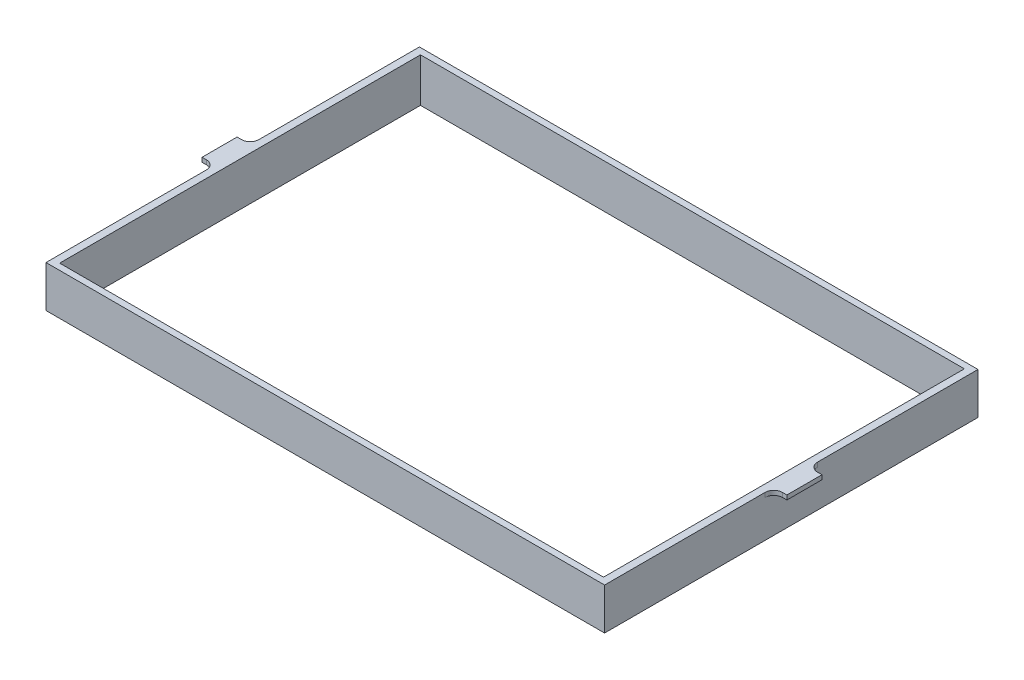
SolidWorks part; units mm, degrees
ref_plane "Front Plane" through (0, 0, 0) normal (0, 0, 1) x (1, 0, 0)
ref_plane "Top Plane" through (0, 0, 0) normal (0, 1, 0) x (1, 0, 0)
ref_plane "Right Plane" through (0, 0, 0) normal (1, 0, 0) x (0, 0, -1)
sketch "Sketch1" plane through (0, 0, 0) normal (0, 1, 0) x (1, 0, 0)
  line L0 (63.88, 42.735) -> (-63.88, 42.735)
  line L1 (63.88, 42.735) -> (63.88, -42.735)
  line L2 (63.88, -42.735) -> (-63.88, -42.735)
  line L3 (-63.88, 42.735) -> (-63.88, -42.735)
  line L4 (63.88, 42.735) -> (-63.88, -42.735) construction
  line L5 (63.88, -42.735) -> (-63.88, 42.735) construction
  point P0 (0, 0)
  dimension "D1" = 127.76
  dimension "D2" = 85.47
sketch "Sketch2" plane through (0, 0, 0) normal (0, 1, 0) x (1, 0, 0)
  line L0 (63.88, 42.735) -> (63.88, -42.735) construction
  line L1 (63.88, -42.735) -> (-63.88, -42.735) construction
  line L2 (-63.88, 42.735) -> (-63.88, -42.735) construction
  line L3 (63.88, 42.735) -> (-63.88, 42.735) construction
  line L4 (63.88, 42.735) -> (63.88, -42.735) construction
  line L5 (63.88, -42.735) -> (-63.88, -42.735) construction
  line L6 (-63.88, 42.735) -> (-63.88, -42.735) construction
  line L7 (63.88, 42.735) -> (-63.88, 42.735) construction
  line L8 (63.78, 42.635) -> (-63.78, 42.635)
  line L9 (-63.78, 42.635) -> (-63.78, -42.635)
  line L10 (63.78, -42.635) -> (-63.78, -42.635)
  line L11 (63.78, 42.635) -> (63.78, -42.635)
  line L12 (63.88, -42.735) -> (-63.88, 42.735) construction
  line L13 (62.1, -41.2) -> (-62.1, -41.2)
  line L14 (62.1, -41.2) -> (62.1, 41.2)
  line L15 (62.1, 41.2) -> (-62.1, 41.2)
  line L16 (-62.1, -41.2) -> (-62.1, 41.2)
  line L17 (62.1, -41.2) -> (-62.1, 41.2) construction
  line L18 (62.1, 41.2) -> (-62.1, -41.2) construction
  point P8 (0, 0)
  dimension "D2" = 82.4
  dimension "D3" = 124.2
  dimension "D1" = 0.1
extrude "Boss-Extrude1" add sketch "Sketch2" along normal blind 10 contours L11 L8 L9 L10 L13 L16 L15 L14
sketch "Sketch3" plane through (-63.78, 0, 0) normal (-1, 0, 0) x (0, 0, 1)
  line L0 (-42.635, 10) -> (42.635, 10) construction
  line L1 (4, 10) -> (-4, 10)
  line L2 (4, 10) -> (4, 9)
  line L3 (4, 9) -> (-4, 9)
  line L4 (-4, 10) -> (-4, 9)
  line L5 (4, 10) -> (-4, 9) construction
  line L6 (4, 9) -> (-4, 10) construction
  line L7 (-42.735, 0) -> (42.735, 0) construction
  point P0 (0, 9.5)
  dimension "D1" = 9
  dimension "D2" = 8
extrude "Boss-Extrude2" add sketch "Sketch3" along normal blind 3
chamfer "Chamfer1" distance 0.5 angle 45 4 edges at (0, 0, 42.635) (63.78, 0, 0) (0, 0, -42.635) (-63.78, 0, 0)
mirror "Mirror1" about plane through (0, 0, 0) normal (1, 0, 0) of "Boss-Extrude2"
fillet "Fillet1" radius 2 4 edges at (63.78, 9.5, -4) (63.78, 9.5, 4) (-63.78, 9.5, -4) (-63.78, 9.5, 4)
